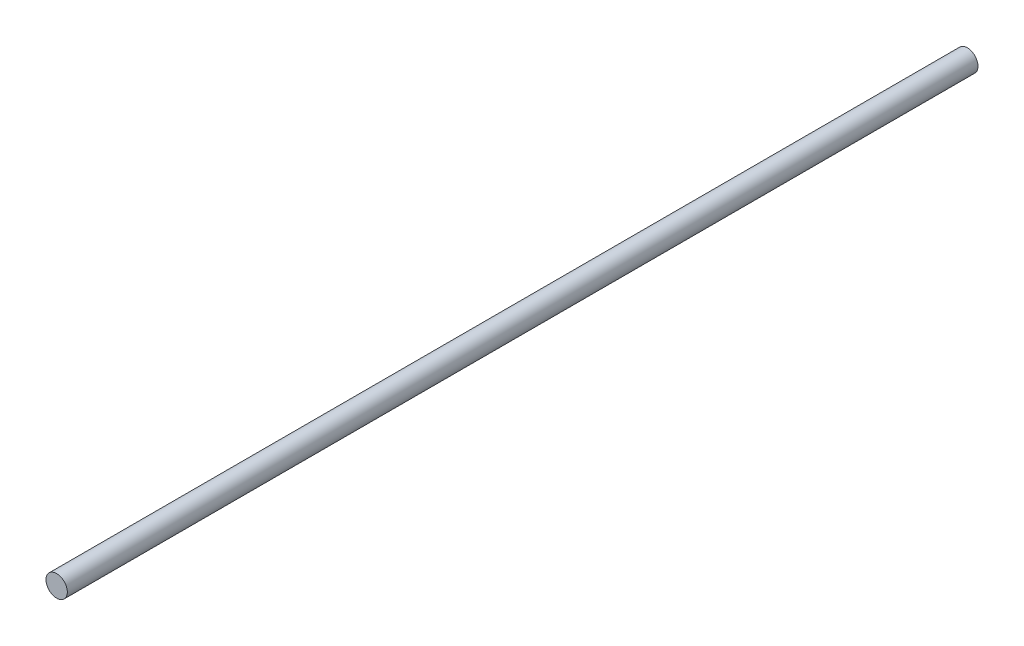
SolidWorks part; units mm, degrees
ref_plane "Plan de face" through (0, 0, 0) normal (0, 0, 1) x (1, 0, 0)
ref_plane "Plan de dessus" through (0, 0, 0) normal (0, 1, 0) x (1, 0, 0)
ref_plane "Plan de droite" through (0, 0, 0) normal (1, 0, 0) x (0, 0, -1)
sketch "Esquisse1" plane through (0, 0, 0) normal (0, 0, 1) x (1, 0, 0)
  circle A0 centre (0, 0) radius 1.5
  dimension "D1" = 3
extrude "Boss.-Extru.1" add sketch "Esquisse1" along normal blind 128
